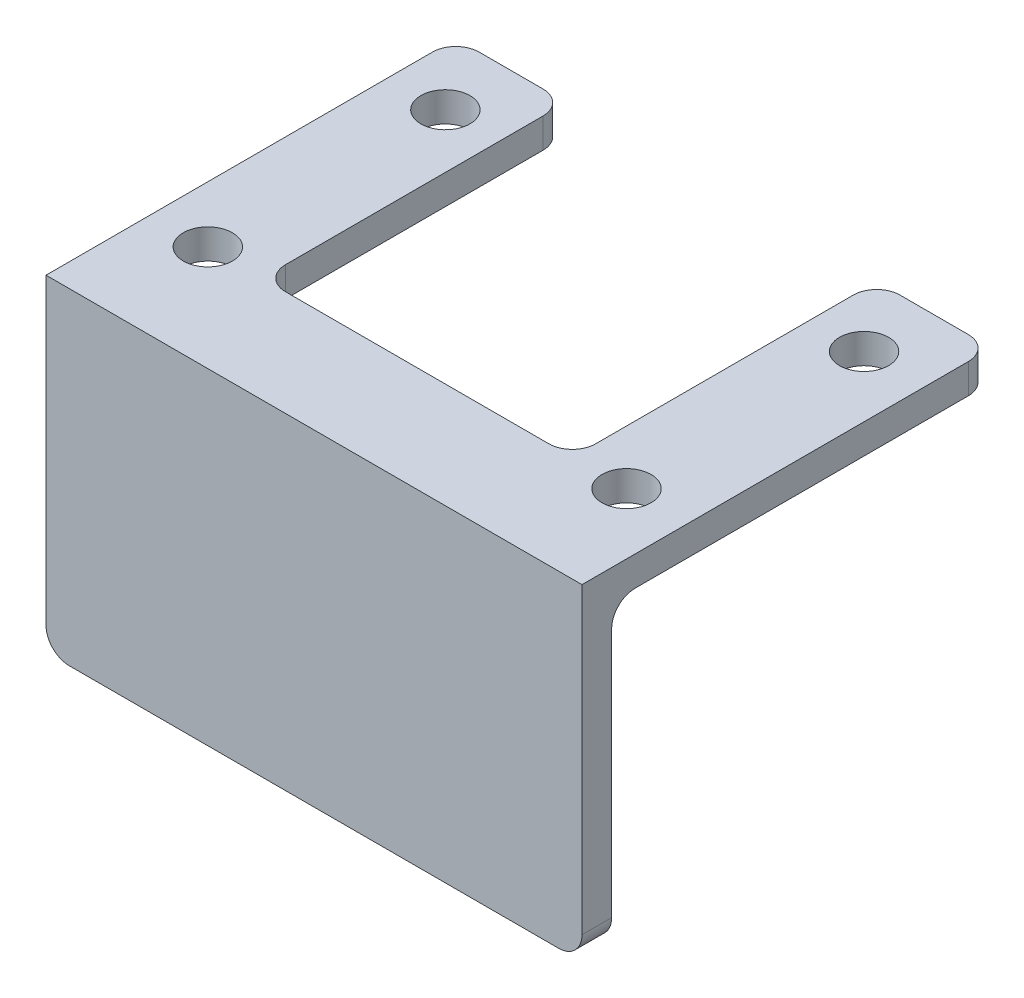
SolidWorks part; units mm, degrees
material "ABS"
ref_plane "X-Y Datum" through (0, 0, 0) normal (0, 0, 1) x (1, 0, 0)
ref_plane "X-Z Datum" through (0, 0, 0) normal (0, 1, 0) x (1, 0, 0)
ref_plane "Y-Z Datum" through (0, 0, 0) normal (1, 0, 0) x (0, 0, -1)
sketch "Sketch1" plane through (0, 0, 0) normal (0, 1, 0) x (1, 0, 0)
  line L0 (15.5691, 29.1106) -> (25.0351, 29.1106)
  line L1 (15.5691, 29.1106) -> (15.5691, -2.1314)
  line L3 (61.4161, 29.1106) -> (61.4161, -2.1314)
  line L4 (22.4951, 23.3956) -> (25.0351, 23.3956) construction
  line L5 (22.4951, 3.0756) -> (25.0351, 3.0756) construction
  line L6 (54.1091, 3.0756) -> (51.5691, 3.0756) construction
  line L7 (54.1091, 23.3956) -> (51.5691, 23.3956) construction
  line L8 (25.0351, 29.1106) -> (25.0351, 3.0756)
  line L9 (25.0351, 3.0756) -> (51.5691, 3.0756)
  line L10 (51.5691, 29.1106) -> (51.5691, 3.0756)
  line L11 (51.5691, 29.1106) -> (61.4161, 29.1106)
  line L12 (15.5691, -2.1314) -> (15.5691, -3.4014)
  line L13 (15.5691, -3.4014) -> (61.4161, -3.4014)
  line L14 (61.4161, -3.4014) -> (61.4161, -2.1314)
  circle A0 centre (20.3951, 23.3956) radius 2.1
  circle A1 centre (20.3951, 3.0756) radius 2.1
  circle A2 centre (56.2091, 23.3956) radius 2.1
  circle A3 centre (56.2091, 3.0756) radius 2.1
extrude "Boss-Extrude1" add sketch "Sketch1" along normal blind 2.54
sketch "Sketch2" plane through (0, 0, 0) normal (0, -1, 0) x (1, 0, 0)
  line L1 (15.5691, 3.4014) -> (61.4161, 3.4014)
  line L2 (15.5691, 3.4014) -> (15.5691, 5.9414)
  line L3 (15.5691, 5.9414) -> (61.4161, 5.9414)
  line L4 (61.4161, 3.4014) -> (61.4161, 5.9414)
extrude "Boss-Extrude2" add sketch "Sketch2" along normal blind 25.4 and the other way through all
fillet "Fillet1" radius 2 9 edges at (15.5691, -25.4, 4.6714) (61.4161, -25.4, 4.6714) (38.4926, 0, 3.4014) (61.4161, 1.27, -29.1106) (51.5691, 1.27, -29.1106) (51.5691, 1.27, -3.0756) (25.0351, 1.27, -3.0756) (25.0351, 1.27, -29.1106) (15.5691, 1.27, -29.1106)
